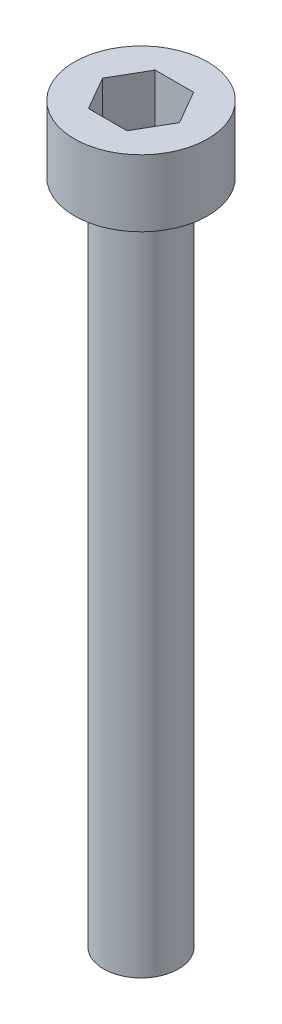
SolidWorks part; units mm, degrees
ref_plane "Plan de face" through (0, 0, 0) normal (0, 0, 1) x (1, 0, 0)
ref_plane "Plan de dessus" through (0, 0, 0) normal (0, 1, 0) x (1, 0, 0)
ref_plane "Plan de droite" through (0, 0, 0) normal (1, 0, 0) x (0, 0, -1)
sketch "Esquisse1" plane through (0, 0, 0) normal (0, 0, 1) x (1, 0, 0)
  line L1 (-1.125, -20) -> (1.125, -20)
  line L2 (-1.125, -20) -> (-1.125, 20)
  line L3 (-1.125, 20) -> (1.125, 20)
  line L4 (1.125, -20) -> (1.125, 20)
  line L5 (-1.125, -20) -> (1.125, 20) construction
  line L6 (-1.125, 20) -> (1.125, -20) construction
  line L7 (1.125, 20) -> (-2.875, 20)
  line L8 (1.125, 20) -> (1.125, 24)
  line L9 (1.125, 24) -> (-2.875, 24)
  line L10 (-2.875, 20) -> (-2.875, 24)
  line L11 (1.125, 20) -> (-2.875, 24) construction
  line L12 (1.125, 24) -> (-2.875, 20) construction
  point P0 (0, 0)
  point P9 (-0.875, 22)
  dimension "D1" = 40
  dimension "D2" = 4
  dimension "D3" = 2.25
  dimension "D4" = 4
revolve "Révolution1" add sketch "Esquisse1" angle 360 about L4
sketch "Esquisse2" plane through (0, 24, 0) normal (0, 1, 0) x (1, 0, 0)
  line L1 (3.4344, 0) -> (2.2797, 2)
  line L2 (2.2797, 2) -> (-0.0297, 2)
  line L3 (-0.0297, 2) -> (-1.1844, 0)
  line L4 (-1.1844, 0) -> (-0.0297, -2)
  line L5 (-0.0297, -2) -> (2.2797, -2)
  line L6 (2.2797, -2) -> (3.4344, 0)
  circle A0 centre (1.125, 0) radius 2 construction
  dimension "D1" = 4
extrude "Enlèv. mat.-Extru.1" cut sketch "Esquisse2" against normal blind 3
